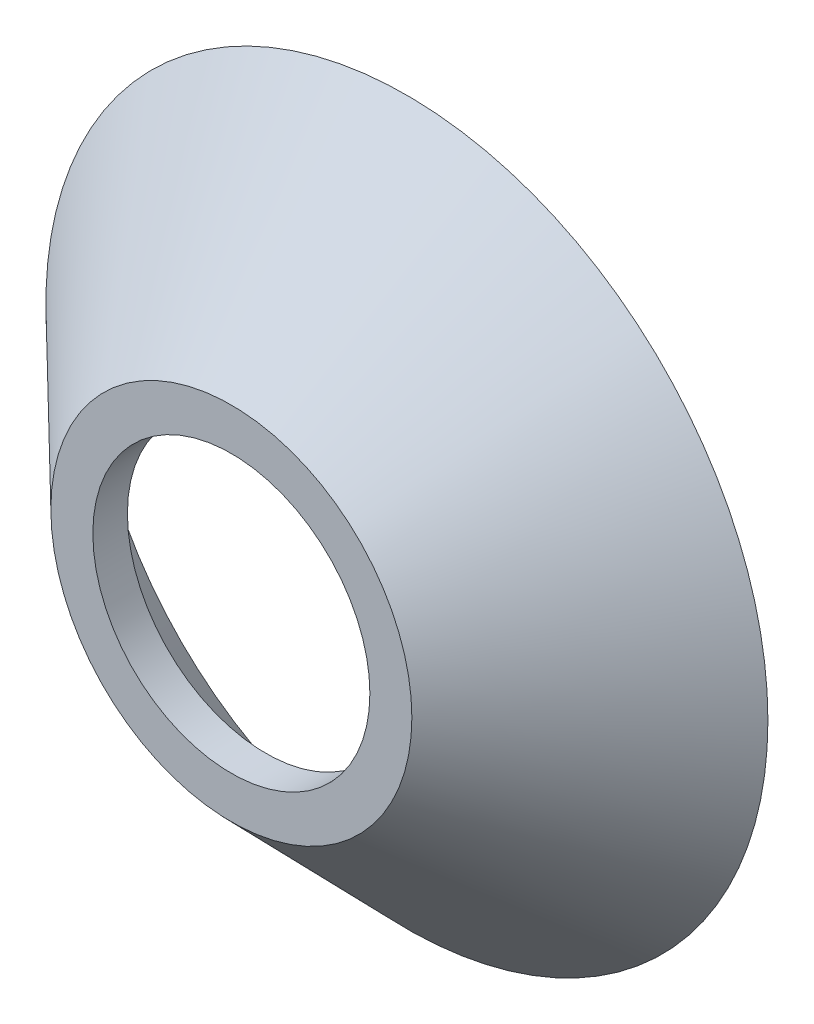
SolidWorks part; units mm, degrees
material "POM Acetal Copolymer"
ref_plane "Front Plane" through (0, 0, 0) normal (0, 0, 1) x (1, 0, 0)
ref_plane "Top Plane" through (0, 0, 0) normal (0, 1, 0) x (1, 0, 0)
ref_plane "Right Plane" through (0, 0, 0) normal (1, 0, 0) x (0, 0, -1)
sketch "Sketch1" plane through (0, 0, 0) normal (0, 1, 0) x (1, 0, 0)
  line L8 (0, 0) -> (0, 55.0933) construction
  line L9 (0, 0) -> (-25.4, 0)
  line L10 (-25.4, 0) -> (-50.8, 24.7001)
  line L11 (-50.8, 24.7001) -> (-44.8579, 24.7001)
  line L12 (-44.8579, 24.7001) -> (-24.4614, 4.8657)
  line L13 (-24.4614, 4.8657) -> (0, 4.8657)
  line L14 (0, 4.8657) -> (0, 0)
  dimension "D1" = 25.4
  dimension "D2" = 101.6
revolve "Revolve1" add sketch "Sketch1" angle 360 about L8
sketch "Sketch2" plane through (0, 0, 0) normal (0, 0, 1) x (1, 0, 0)
  circle A0 centre (0, 0) radius 19.4922
extrude "Cut-Extrude2" cut sketch "Sketch2" against normal up to next
